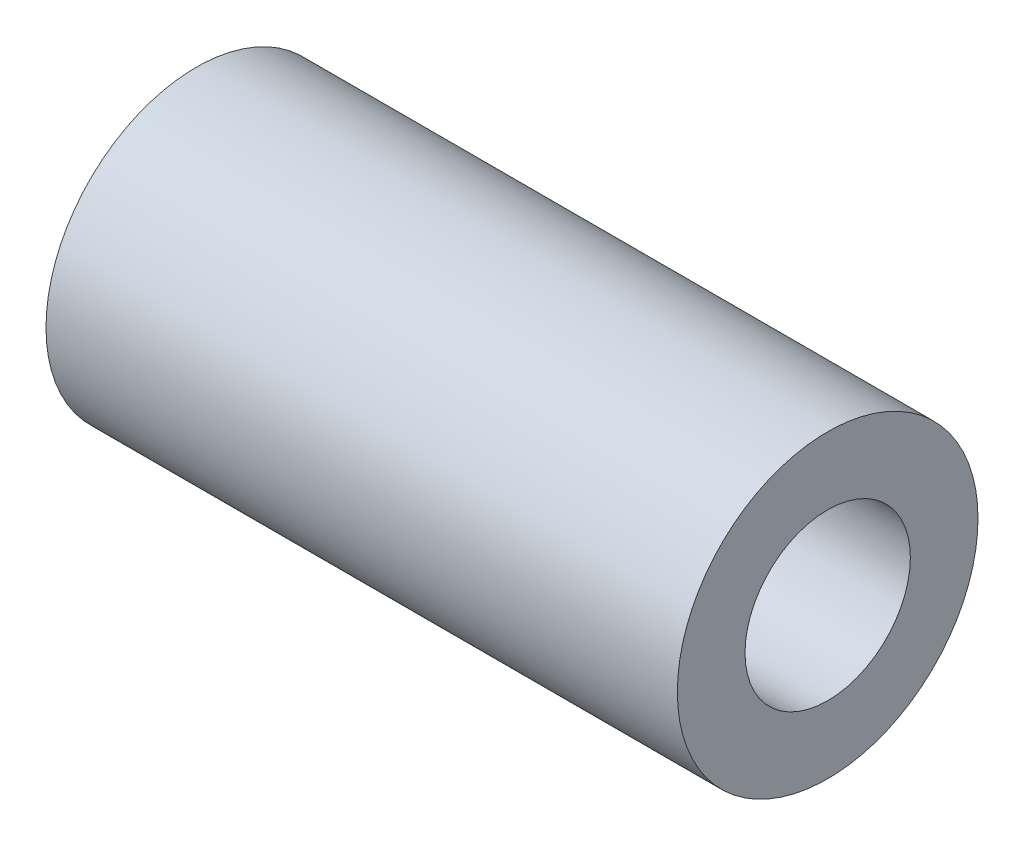
SolidWorks part; units mm, degrees
ref_plane "Front Plane" through (0, 0, 0) normal (0, 0, 1) x (1, 0, 0)
ref_plane "Top Plane" through (0, 0, 0) normal (0, 1, 0) x (1, 0, 0)
ref_plane "Right Plane" through (0, 0, 0) normal (1, 0, 0) x (0, 0, -1)
sketch "Sketch1" plane through (0, 0, 0) normal (1, 0, 0) x (0, 0, -1)
  circle A0 centre (0, 0) radius 2.75
  circle A1 centre (0, 0) radius 5
  dimension "D1" = 5.5
  dimension "D2" = 10
extrude "Boss-Extrude1" add sketch "Sketch1" along normal blind 21
